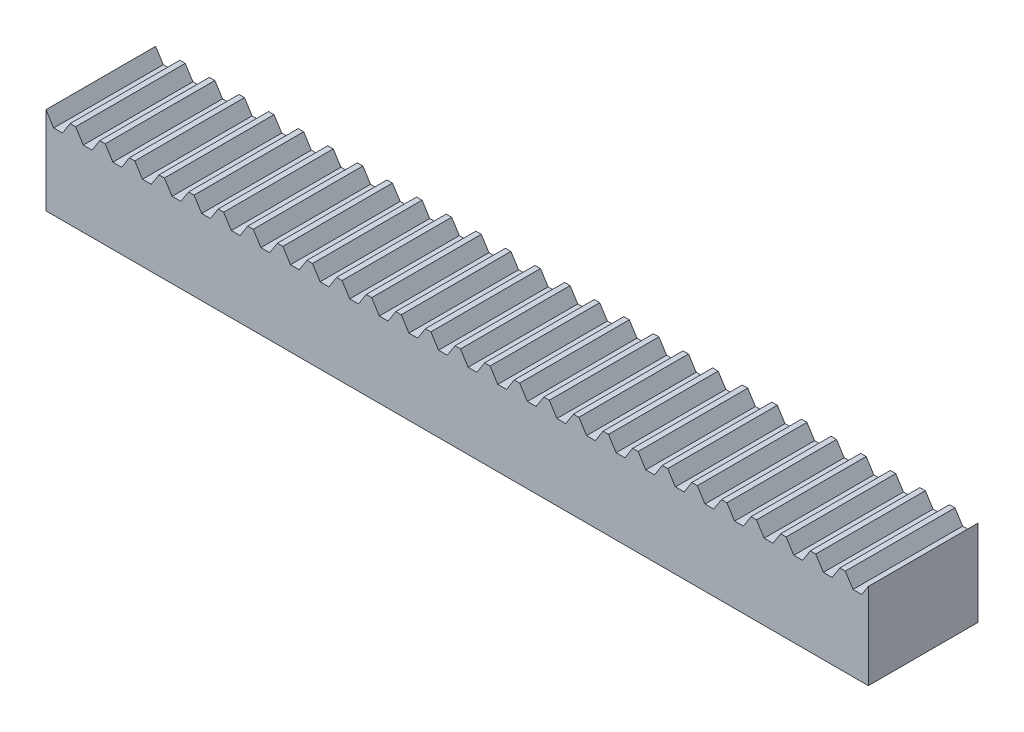
SolidWorks part; units mm, degrees
ref_plane "Front Plane" through (0, 0, 0) normal (0, 0, 1) x (1, 0, 0)
ref_plane "Top Plane" through (0, 0, 0) normal (0, 1, 0) x (1, 0, 0)
ref_plane "Right Plane" through (0, 0, 0) normal (1, 0, 0) x (0, 0, -1)
sketch "Sketch2" plane through (0, 0, 0) normal (0, 1, 0) x (1, 0, 0)
  line L1 (-37.5, 5) -> (37.5, 5)
  line L2 (-37.5, 5) -> (-37.5, -5)
  line L3 (-37.5, -5) -> (37.5, -5)
  line L4 (37.5, 5) -> (37.5, -5)
  line L5 (-37.5, 5) -> (37.5, -5) construction
  line L6 (-37.5, -5) -> (37.5, 5) construction
  point P0 (0, 0)
  dimension "D1" = 10
  dimension "D2" = 75
extrude "Boss-Extrude1" add sketch "Sketch2" along normal blind 8
sketch "Sketch3" plane through (0, 0, 5) normal (0, 0, 1) x (1, 0, 0)
  line L0 (-36.8, 6.9) -> (-36, 6.9)
  line L2 (-37.5, 8) -> (-36.8, 6.9)
  line L3 (-36.4, 6.9) -> (-36.4, 8) construction
  line L4 (-35.3, 8) -> (-36, 6.9)
  line L5 (-37.5, 8) -> (-35.3, 8)
  line L6 (-37.5, 8) -> (-37.5, 0) construction
  dimension "D1" = 0.7
  dimension "D2" = 0.4
  dimension "D3" = 1.1
extrude "Cut-Extrude1" cut sketch "Sketch3" against normal blind 15
pattern_linear "LPattern1" count 31 spacing 2.7 along (1, 0, 0) of "Cut-Extrude1"
